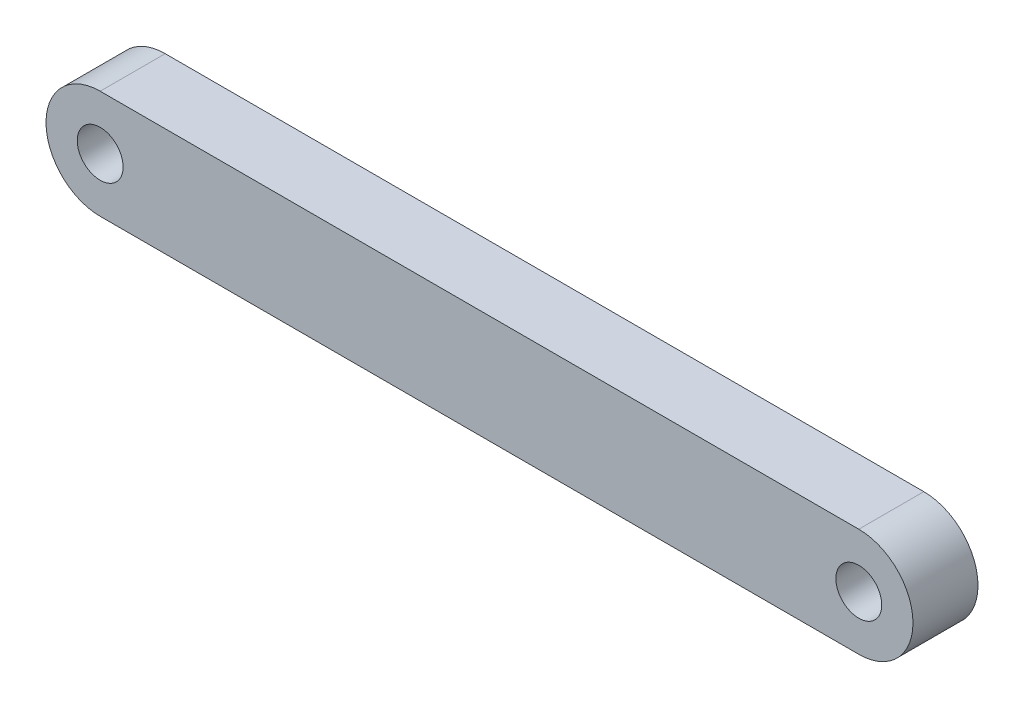
SolidWorks part; units mm, degrees
ref_plane "Front Plane" through (0, 0, 0) normal (0, 0, 1) x (1, 0, 0)
ref_plane "Top Plane" through (0, 0, 0) normal (0, 1, 0) x (1, 0, 0)
ref_plane "Right Plane" through (0, 0, 0) normal (1, 0, 0) x (0, 0, -1)
sketch "Sketch1" plane through (0, 0, 0) normal (0, 0, 1) x (1, 0, 0)
  line L0 (-769.9013, 0) -> (37725.162, 0) construction
  line L1 (-52.5, 7.5) -> (52.5, 7.5)
  line L3 (-52.5, -7.5) -> (52.5, -7.5)
  line L5 (0, -1000) -> (0, 49000) construction
  circle A0 centre (52.5, 0) radius 3.175
  circle A1 centre (-52.5, 0) radius 3.175
  arc A3 (52.5, -7.5) -> (52.5, 7.5) centre (52.5, 0) ccw
  arc A4 (-52.5, -7.5) -> (-52.5, 7.5) centre (-52.5, 0) cw
  point P0 (51.2603, -7.3968)
  dimension "D3" = 6.35
  dimension "D1" = 7.5
  dimension "D5" = 105
extrude "Boss-Extrude1" add sketch "Sketch1" along normal mid plane 9
